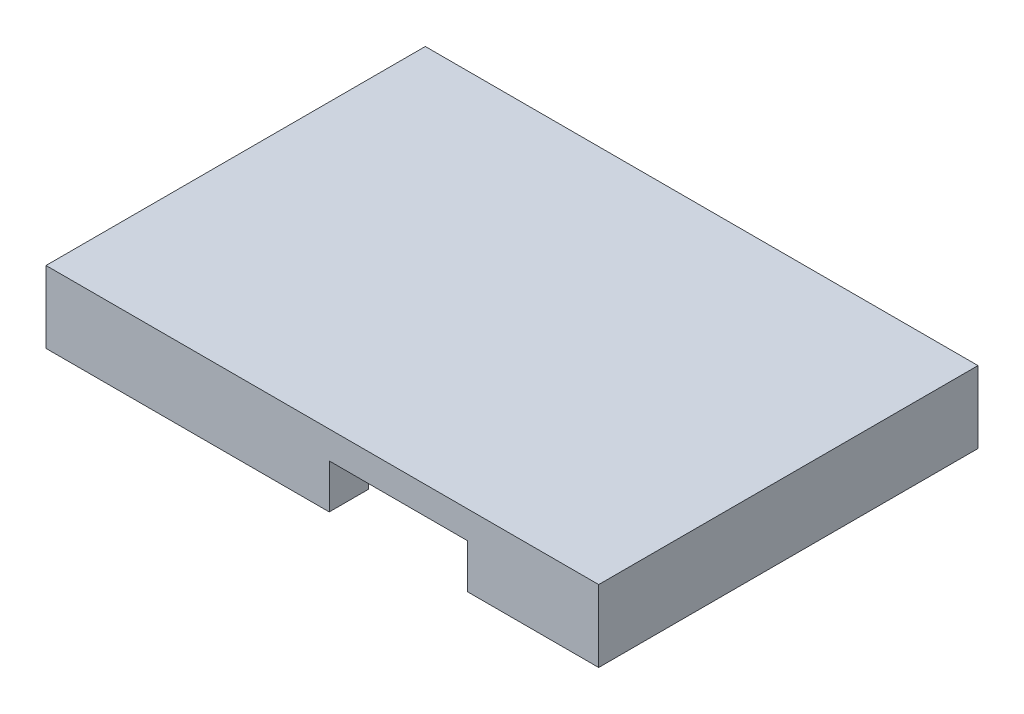
SolidWorks part; units mm, degrees
material "ABS"
ref_plane "Front Plane" through (0, 0, 0) normal (0, 0, 1) x (1, 0, 0)
ref_plane "Top Plane" through (0, 0, 0) normal (0, 1, 0) x (1, 0, 0)
ref_plane "Right Plane" through (0, 0, 0) normal (1, 0, 0) x (0, 0, -1)
sketch "Sketch1" plane through (0, 0, 0) normal (0, 1, 0) x (1, 0, 0)
  line L0 (10.5, -10.873) -> (10.5, -13.7259)
  line L1 (10.5, -13.7259) -> (20, -13.7259)
  line L2 (20, -13.7259) -> (20, 13.7259)
  line L3 (20, 13.7259) -> (-20, 13.7259)
  line L4 (-20, 13.7259) -> (-20, -13.7259)
  line L5 (-20, -13.7259) -> (0.5, -13.7259)
  line L6 (0.5, -13.7259) -> (0.5, -10.873)
  line L7 (0.5, -10.873) -> (-11.5, -10.873)
  line L8 (-11.5, -10.873) -> (-11.5, -6.873)
  line L9 (-11.5, -6.873) -> (-16, -6.873)
  line L10 (-16, -6.873) -> (-16, -4.873)
  line L11 (-16, -4.873) -> (-11.5, -4.873)
  line L12 (-11.5, -4.873) -> (-11.5, 10.627)
  line L13 (-11.5, 10.627) -> (11.5, 10.627)
  line L14 (11.5, 10.627) -> (11.5, -4.873)
  line L15 (11.5, -4.873) -> (16, -4.873)
  line L16 (16, -4.873) -> (16, -6.873)
  line L17 (16, -6.873) -> (11.5, -6.873)
  line L18 (11.5, -6.873) -> (11.5, -10.873)
  line L19 (11.5, -10.873) -> (10.5, -10.873)
extrude "Boss-Extrude1" add sketch "Sketch1" along normal blind 3.2
sketch "Sketch2" plane through (0, 3.2, 0) normal (0, 1, 0) x (1, 0, 0)
  line L1 (-20, 13.7259) -> (20, 13.7259)
  line L2 (-20, 13.7259) -> (-20, -13.7259)
  line L3 (-20, -13.7259) -> (20, -13.7259)
  line L4 (20, 13.7259) -> (20, -13.7259)
extrude "Boss-Extrude2" add sketch "Sketch2" along normal blind 2
